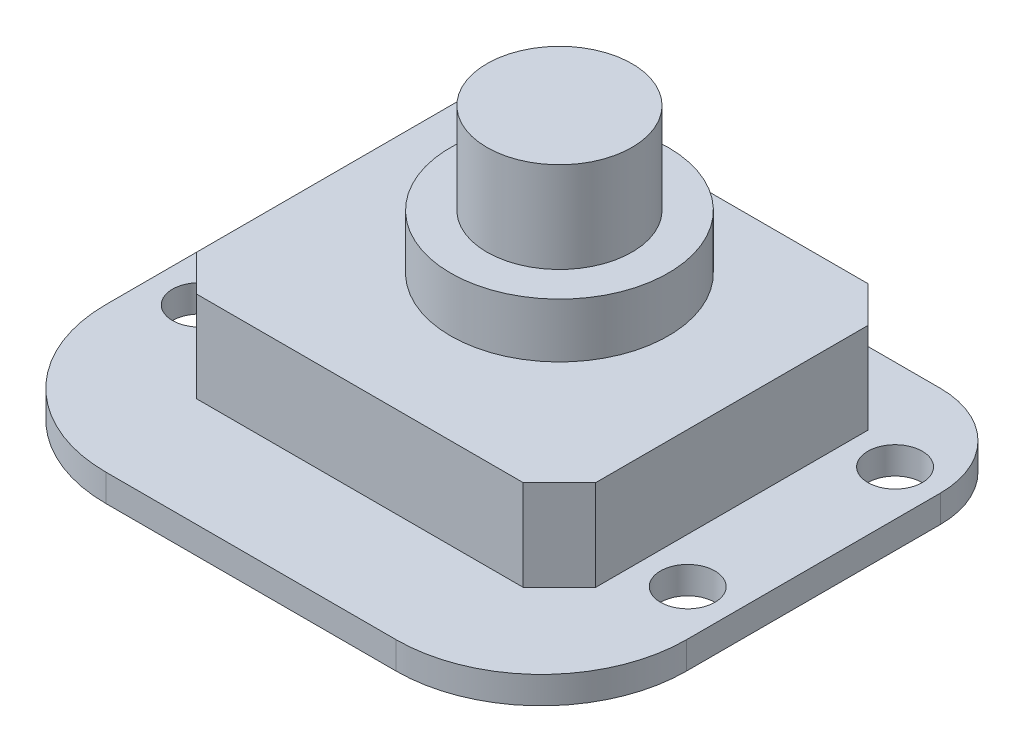
SolidWorks part; units mm, degrees
ref_plane "前视基准面" through (0, 0, 0) normal (0, 0, 1) x (1, 0, 0)
ref_plane "上视基准面" through (0, 0, 0) normal (0, 1, 0) x (1, 0, 0)
ref_plane "右视基准面" through (0, 0, 0) normal (1, 0, 0) x (0, 0, -1)
other "Configuration Table"
sketch "草图1" plane through (0, 0, 0) normal (0, 1, 0) x (1, 0, 0)
  line L1 (-11, 13.5) -> (11, 13.5)
  line L2 (-16, 8.5) -> (-16, -5.5)
  line L3 (-8, -13.5) -> (8, -13.5)
  line L4 (16, 8.5) -> (16, -5.5)
  arc A0 (16, 8.5) -> (11, 13.5) centre (11, 8.5) ccw
  arc A1 (-16, 8.5) -> (-11, 13.5) centre (-11, 8.5) cw
  arc A2 (8, -13.5) -> (16, -5.5) centre (8, -5.5) ccw
  arc A3 (-8, -13.5) -> (-16, -5.5) centre (-8, -5.5) cw
  circle A4 centre (-13.4, 8.5) radius 1.5
  circle A5 centre (13.5, 8.5) radius 1.5
  circle A6 centre (-13.4, -2.93) radius 1.5
  circle A7 centre (13.5, -2.93) radius 1.5
  point P7 (16, 13.5)
  point P10 (-16, 13.5)
  dimension "D5" = 5
  dimension "D6" = 8
  dimension "D7" = 13.4
  dimension "D8" = 13.5
  dimension "D9" = 11.43
  dimension "D1" = 32
  dimension "D2" = 27
  dimension "D3" = 16
  dimension "D4" = 13.5
  dimension "D10" = 11.43
extrude "凸台-拉伸1" add sketch "草图1" along normal blind 1.5
sketch "草图2" plane through (0, 1.5, 0) normal (0, 1, 0) x (1, 0, 0)
  line L0 (11, 13.5) -> (-11, 13.5) construction
  line L1 (-9, 11.5) -> (9, 11.5)
  line L2 (-11, 9.5) -> (-11, -5.5)
  line L3 (-9, -7.5) -> (9, -7.5)
  line L4 (11, 9.5) -> (11, -5.5)
  line L5 (-8, -13.5) -> (8, -13.5) construction
  line L6 (16, -5.5) -> (16, 8.5) construction
  line L7 (-16, 8.5) -> (-16, -5.5) construction
  line L8 (-9, 11.5) -> (-11, 9.5)
  line L9 (9, 11.5) -> (11, 9.5)
  line L10 (11, -5.5) -> (9, -7.5)
  line L11 (-11, -5.5) -> (-9, -7.5)
  point P0 (-11, 11.5)
  point P1 (11, -7.5)
  point P2 (-11, -7.5)
  point P3 (11, 11.5)
  dimension "D1" = 2
  dimension "D2" = 6
  dimension "D3" = 5
  dimension "D4" = 5
extrude "凸台-拉伸2" add sketch "草图2" along normal blind 5
sketch "草图3" plane through (0, 6.5, 0) normal (0, 1, 0) x (1, 0, 0)
  line L0 (11, -5.5) -> (11, 9.5) construction
  line L3 (9, 11.5) -> (-9, 11.5) construction
  circle A0 centre (0, 3.5) radius 6
  dimension "D1" = 11
  dimension "D2" = 8
extrude "凸台-拉伸3" add sketch "草图3" along normal blind 3
sketch "草图4" plane through (0, 9.5, 0) normal (0, 1, 0) x (1, 0, 0)
  circle A0 centre (0, 3.5) radius 4
  circle A1 centre (0, 3.5) radius 6 construction
  dimension "D1" = 0
extrude "凸台-拉伸4" add sketch "草图4" along normal blind 5
